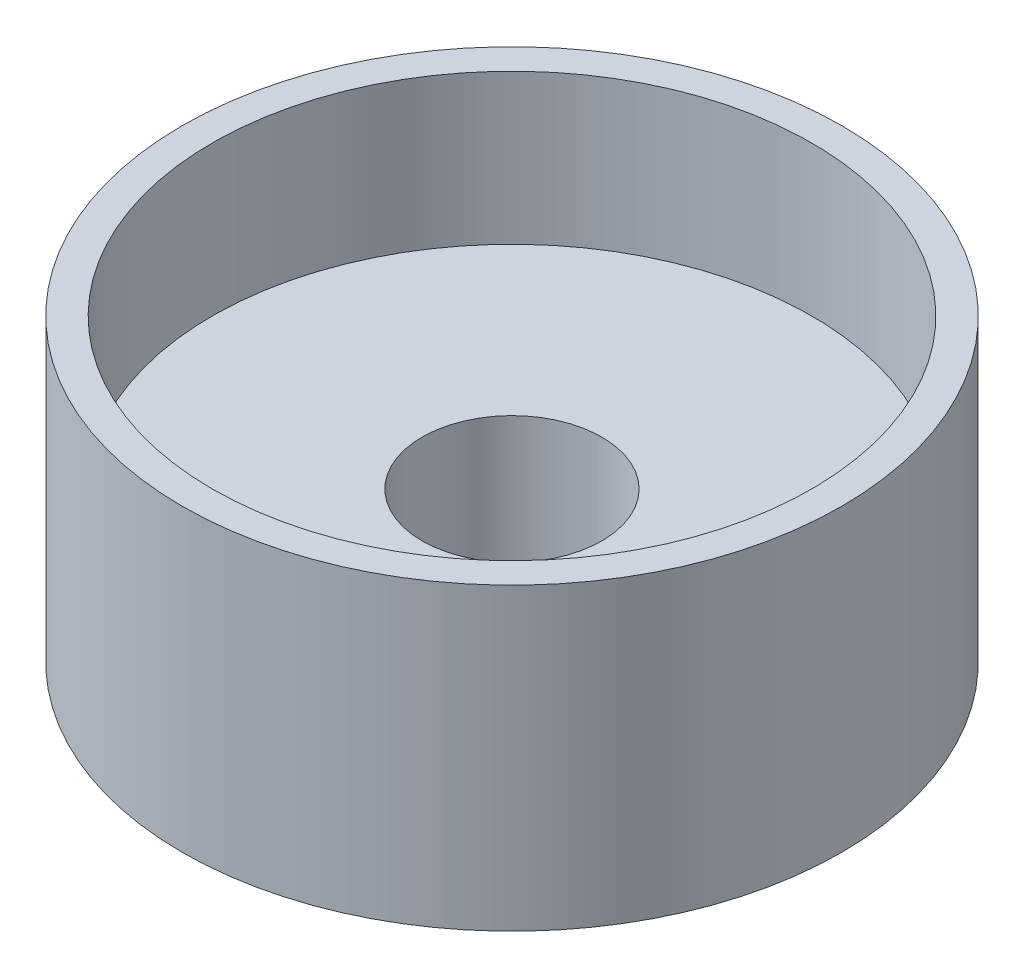
SolidWorks part; units mm, degrees
ref_plane "Front Plane" through (0, 0, 0) normal (0, 0, 1) x (1, 0, 0)
ref_plane "Top Plane" through (0, 0, 0) normal (0, 1, 0) x (1, 0, 0)
ref_plane "Right Plane" through (0, 0, 0) normal (1, 0, 0) x (0, 0, -1)
sketch "Sketch1" plane through (0, 0, 0) normal (0, 1, 0) x (1, 0, 0)
  circle A0 centre (0, 0) radius 11
  dimension "D1" = 22
extrude "Boss-Extrude1" add sketch "Sketch1" along normal blind 10
sketch "Sketch2" plane through (0, 0, 0) normal (0, 1, 0) x (1, 0, 0)
  circle A0 centre (0, 0) radius 3
  dimension "D1" = 6
extrude "Cut-Extrude1" cut sketch "Sketch2" along normal blind 20
sketch "Sketch5" plane through (0, 10, 0) normal (0, 1, 0) x (1, 0, 0)
  circle A0 centre (0, 0) radius 10
  dimension "D1" = 20
extrude "Cut-Extrude3" cut sketch "Sketch5" against normal blind 5
sketch "Sketch4" plane through (0, 0, 0) normal (1, 0, 0) x (0, 0, -1)
  line L6 (0, 0) -> (0, 4.7947) construction
  line L7 (-10, 6.06) -> (-10, 5.46)
  line L8 (-10, 10) -> (-10, 5) construction
  line L10 (-9.5, 5.6525) -> (-9.5, 5.8675)
  line L12 (-9.6457, 5.46) -> (-10, 5.36)
  line L13 (-9.6457, 5.46) -> (-10, 5.46) construction
  line L16 (-10, 5.36) -> (-10, 5.46)
  line L17 (-9.6457, 6.06) -> (-10, 6.16)
  line L18 (-10, 6.16) -> (-10, 6.06)
  line L19 (-9.6457, 6.06) -> (-10, 6.06) construction
  line L21 (11, 10) -> (-11, 10) construction
  arc A2 (-9.6457, 5.46) -> (-9.5, 5.6525) centre (-9.7, 5.6525) ccw
  arc A3 (-9.5, 5.8675) -> (-9.6457, 6.06) centre (-9.7, 5.8675) ccw
  point P4 (-10, 5.76)
  point P22 (-9.5, 5.76)
  dimension "D4" = 0.2
  dimension "D1" = 0.1
  dimension "D2" = 0.6
  dimension "D3" = 0.1
  dimension "D5" = 0.5
  dimension "D6" = 4.24
revolve "Revolve1" [suppressed] add sketch "Sketch4" angle 360 about L6
